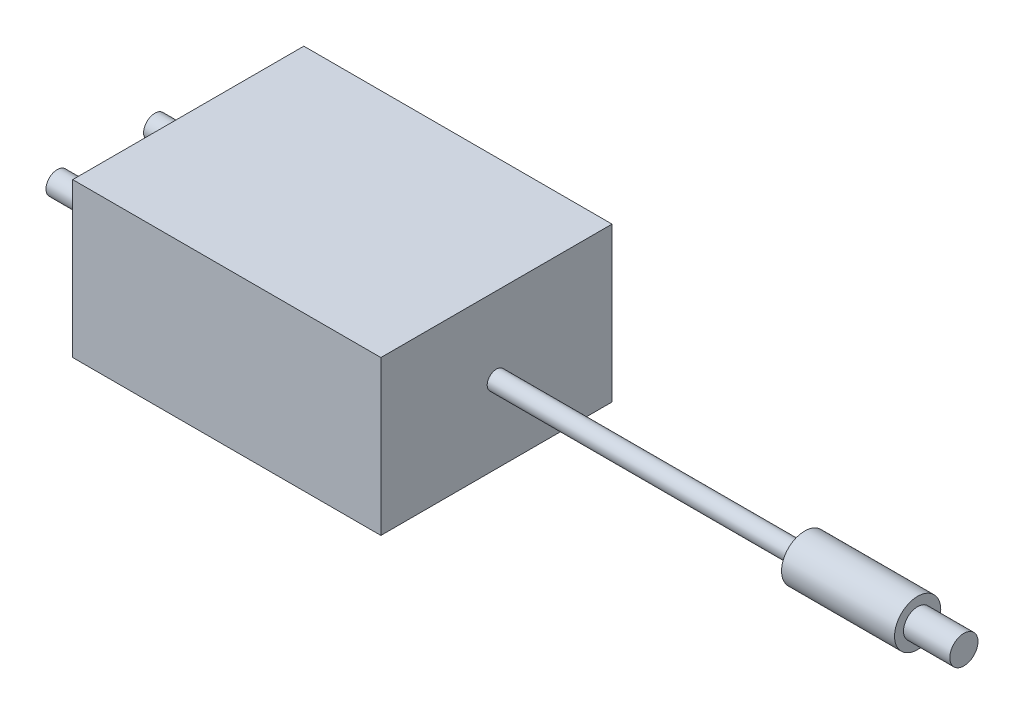
SolidWorks part; units mm, degrees
ref_plane "Front Plane" through (0, 0, 0) normal (0, 0, 1) x (1, 0, 0)
ref_plane "Top Plane" through (0, 0, 0) normal (0, 1, 0) x (1, 0, 0)
ref_plane "Right Plane" through (0, 0, 0) normal (1, 0, 0) x (0, 0, -1)
sketch "SK Adapter body" plane through (0, 0, 0) normal (0, 1, 0) x (1, 0, 0)
  line L1 (0, 45) -> (60, 45)
  line L2 (0, 45) -> (0, 0)
  line L3 (0, 0) -> (60, 0)
  line L4 (60, 45) -> (60, 0)
extrude "Adapter body" add sketch "SK Adapter body" along normal blind 30 separate body
sketch "SK Mains pins" plane through (0, 0, 0) normal (1, 0, 0) x (0, 0, -1)
  circle A0 centre (13, 15) radius 2.2
  circle A1 centre (32, 15) radius 2.2
extrude "Mains pins" add sketch "SK Mains pins" along normal blind 16 from offset 16 separate body
sketch "SK DC lead" plane through (0, 0, 0) normal (1, 0, 0) x (0, 0, -1)
  circle A0 centre (22.5, 15) radius 1.8
extrude "DC lead" add sketch "SK DC lead" along normal blind 60 from offset 60 separate body
sketch "SK Barrel plug" plane through (0, 0, 0) normal (1, 0, 0) x (0, 0, -1)
  circle A0 centre (22.5, 15) radius 4.5
extrude "Barrel plug" add sketch "SK Barrel plug" along normal blind 22 from offset 120 separate body
sketch "SK Plug tip" plane through (0, 0, 0) normal (1, 0, 0) x (0, 0, -1)
  circle A0 centre (22.5, 15) radius 2.75
extrude "Plug tip" add sketch "SK Plug tip" along normal blind 9 from offset 142 separate body
